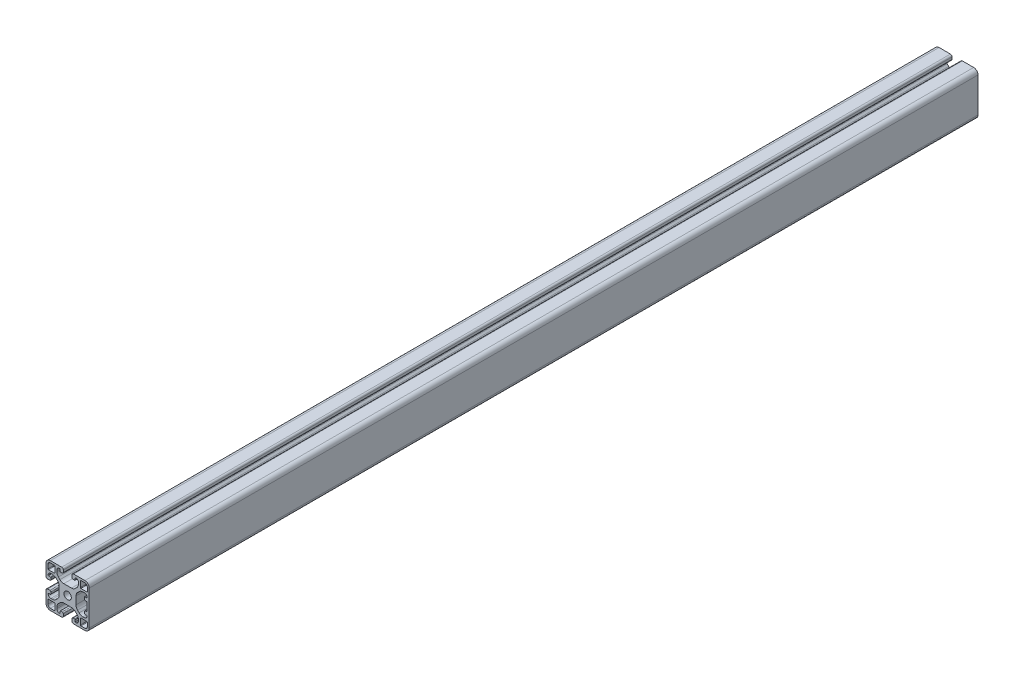
SolidWorks part; units mm, degrees
ref_plane "Piano frontale" through (0, 0, 0) normal (0, 0, 1) x (1, 0, 0)
ref_plane "Piano superiore" through (0, 0, 0) normal (0, 1, 0) x (1, 0, 0)
ref_plane "Piano destro" through (0, 0, 0) normal (1, 0, 0) x (0, 0, -1)
ref_plane "Piano1" through (0, 0, -340) normal (0, 0, -1) x (-1, 0, 0)
sketch "Schizzo1" plane through (0, 0, -340) normal (0, 0, -1) x (-1, 0, 0)
  line L0 (-12.3, -18.2) -> (-16, -18.2)
  line L1 (-18.2, -16) -> (-18.2, -12.3)
  line L2 (-17.7, -11.8) -> (-12.3, -11.8)
  line L3 (-11.8, -12.3) -> (-11.8, -17.7)
  line L4 (-11.8, 17.7) -> (-11.8, 12.3)
  line L5 (-12.3, 11.8) -> (-17.7, 11.8)
  line L6 (-18.2, 12.3) -> (-18.2, 16)
  line L7 (-16, 18.2) -> (-12.3, 18.2)
  line L8 (18.2, 16) -> (18.2, 12.3)
  line L9 (17.7, 11.8) -> (12.3, 11.8)
  line L10 (11.8, 12.3) -> (11.8, 17.7)
  line L11 (12.3, 18.2) -> (16, 18.2)
  line L12 (6.5, -15.5) -> (5, -15.5)
  line L13 (4, -16.5) -> (4, -18.5)
  line L14 (5.5, -20) -> (16, -20)
  line L15 (20, -16) -> (20, -5.5)
  line L16 (18.5, -4) -> (16.5, -4)
  line L17 (15.5, -5) -> (15.5, -6.5)
  line L18 (16, -7) -> (17.55, -7)
  line L19 (18, -7.45) -> (18, -7.5)
  line L20 (15.5, -10) -> (14.1924, -10)
  line L21 (10.6569, -8.5355) -> (9.2145, -7.0931)
  line L22 (7.75, -3.5576) -> (7.75, 3.5576)
  line L23 (9.2145, 7.0931) -> (10.6569, 8.5355)
  line L24 (14.1924, 10) -> (15.5, 10)
  line L25 (18, 7.5) -> (18, 7.45)
  line L26 (17.55, 7) -> (16, 7)
  line L27 (15.5, 6.5) -> (15.5, 5)
  line L28 (16.5, 4) -> (18.5, 4)
  line L29 (20, 5.5) -> (20, 16)
  line L30 (16, 20) -> (5.5, 20)
  line L31 (4, 18.5) -> (4, 16.5)
  line L32 (5, 15.5) -> (6.5, 15.5)
  line L33 (7, 16) -> (7, 17.55)
  line L34 (7.45, 18) -> (7.5, 18)
  line L35 (10, 15.5) -> (10, 14.1924)
  line L36 (8.5355, 10.6569) -> (7.0931, 9.2145)
  line L37 (3.5576, 7.75) -> (-3.5576, 7.75)
  line L38 (-7.0931, 9.2145) -> (-8.5355, 10.6569)
  line L39 (-10, 14.1924) -> (-10, 15.5)
  line L40 (-7.5, 18) -> (-7.45, 18)
  line L41 (-7, 17.55) -> (-7, 16)
  line L42 (-6.5, 15.5) -> (-5, 15.5)
  line L43 (-4, 16.5) -> (-4, 18.5)
  line L44 (-5.5, 20) -> (-16, 20)
  line L45 (-20, 16) -> (-20, -16)
  line L46 (-16, -20) -> (-5.5, -20)
  line L47 (-4, -18.5) -> (-4, -16.5)
  line L48 (-5, -15.5) -> (-6.5, -15.5)
  line L49 (-7, -16) -> (-7, -17.55)
  line L50 (-7.45, -18) -> (-7.5, -18)
  line L51 (-10, -15.5) -> (-10, -14.1924)
  line L52 (-8.5355, -10.6569) -> (-7.0931, -9.2145)
  line L53 (-3.5576, -7.75) -> (3.5576, -7.75)
  line L54 (7.0931, -9.2145) -> (8.5355, -10.6569)
  line L55 (10, -14.1924) -> (10, -15.5)
  line L56 (7.5, -18) -> (7.45, -18)
  line L57 (7, -17.55) -> (7, -16)
  line L58 (18.2, -12.3) -> (18.2, -16)
  line L59 (16, -18.2) -> (12.3, -18.2)
  line L60 (11.8, -17.7) -> (11.8, -12.3)
  line L61 (12.3, -11.8) -> (17.7, -11.8)
  line L62 (-16, 7) -> (-17.5, 7)
  line L63 (-15.5, 10) -> (-14.1924, 10)
  line L64 (-10.6569, 8.5355) -> (-9.2145, 7.0931)
  line L65 (-7.75, 3.5576) -> (-7.75, -3.5576)
  line L66 (-9.2145, -7.0931) -> (-10.6569, -8.5355)
  line L67 (-14.1924, -10) -> (-15.5, -10)
  line L68 (-17.5, -7) -> (-16, -7)
  line L69 (-15.5, -6.5) -> (-15.5, -5)
  line L70 (-16.5, -4) -> (-17.5, -4)
  line L71 (-18, -3.5) -> (-18, 3.5)
  line L72 (-17.5, 4) -> (-16.5, 4)
  line L73 (-15.5, 5) -> (-15.5, 6.5)
  arc A0 (-16, -18.2) -> (-18.2, -16) centre (-16, -16) cw
  arc A1 (-18.2, -12.3) -> (-17.7, -11.8) centre (-17.7, -12.3) cw
  arc A2 (-12.3, -11.8) -> (-11.8, -12.3) centre (-12.3, -12.3) cw
  arc A3 (-11.8, -17.7) -> (-12.3, -18.2) centre (-12.3, -17.7) cw
  arc A4 (-12.3, 18.2) -> (-11.8, 17.7) centre (-12.3, 17.7) cw
  arc A5 (-11.8, 12.3) -> (-12.3, 11.8) centre (-12.3, 12.3) cw
  arc A6 (-17.7, 11.8) -> (-18.2, 12.3) centre (-17.7, 12.3) cw
  arc A7 (-18.2, 16) -> (-16, 18.2) centre (-16, 16) cw
  arc A8 (16, 18.2) -> (18.2, 16) centre (16, 16) cw
  arc A9 (18.2, 12.3) -> (17.7, 11.8) centre (17.7, 12.3) cw
  arc A10 (12.3, 11.8) -> (11.8, 12.3) centre (12.3, 12.3) cw
  arc A11 (11.8, 17.7) -> (12.3, 18.2) centre (12.3, 17.7) cw
  arc A12 (5, -15.5) -> (4, -16.5) centre (5, -16.5) ccw
  arc A13 (4, -18.5) -> (5.5, -20) centre (5.5, -18.5) ccw
  arc A14 (16, -20) -> (20, -16) centre (16, -16) ccw
  arc A15 (20, -5.5) -> (18.5, -4) centre (18.5, -5.5) ccw
  arc A16 (16.5, -4) -> (15.5, -5) centre (16.5, -5) ccw
  arc A17 (15.5, -6.5) -> (16, -7) centre (16, -6.5) ccw
  arc A18 (17.55, -7) -> (18, -7.45) centre (17.55, -7.45) cw
  arc A19 (18, -7.5) -> (15.5, -10) centre (15.5, -7.5) cw
  arc A20 (14.1924, -10) -> (10.6569, -8.5355) centre (14.1924, -5) cw
  arc A21 (9.2145, -7.0931) -> (7.75, -3.5576) centre (12.75, -3.5576) cw
  arc A22 (7.75, 3.5576) -> (9.2145, 7.0931) centre (12.75, 3.5576) cw
  arc A23 (10.6569, 8.5355) -> (14.1924, 10) centre (14.1924, 5) cw
  arc A24 (15.5, 10) -> (18, 7.5) centre (15.5, 7.5) cw
  arc A25 (18, 7.45) -> (17.55, 7) centre (17.55, 7.45) cw
  arc A26 (16, 7) -> (15.5, 6.5) centre (16, 6.5) ccw
  arc A27 (15.5, 5) -> (16.5, 4) centre (16.5, 5) ccw
  arc A28 (18.5, 4) -> (20, 5.5) centre (18.5, 5.5) ccw
  arc A29 (20, 16) -> (16, 20) centre (16, 16) ccw
  arc A30 (5.5, 20) -> (4, 18.5) centre (5.5, 18.5) ccw
  arc A31 (4, 16.5) -> (5, 15.5) centre (5, 16.5) ccw
  arc A32 (6.5, 15.5) -> (7, 16) centre (6.5, 16) ccw
  arc A33 (7, 17.55) -> (7.45, 18) centre (7.45, 17.55) cw
  arc A34 (7.5, 18) -> (10, 15.5) centre (7.5, 15.5) cw
  arc A35 (10, 14.1924) -> (8.5355, 10.6569) centre (5, 14.1924) cw
  arc A36 (7.0931, 9.2145) -> (3.5576, 7.75) centre (3.5576, 12.75) cw
  arc A37 (-3.5576, 7.75) -> (-7.0931, 9.2145) centre (-3.5576, 12.75) cw
  arc A38 (-8.5355, 10.6569) -> (-10, 14.1924) centre (-5, 14.1924) cw
  arc A39 (-10, 15.5) -> (-7.5, 18) centre (-7.5, 15.5) cw
  arc A40 (-7.45, 18) -> (-7, 17.55) centre (-7.45, 17.55) cw
  arc A41 (-7, 16) -> (-6.5, 15.5) centre (-6.5, 16) ccw
  arc A42 (-5, 15.5) -> (-4, 16.5) centre (-5, 16.5) ccw
  arc A43 (-4, 18.5) -> (-5.5, 20) centre (-5.5, 18.5) ccw
  arc A44 (-16, 20) -> (-20, 16) centre (-16, 16) ccw
  arc A45 (-20, -16) -> (-16, -20) centre (-16, -16) ccw
  arc A46 (-5.5, -20) -> (-4, -18.5) centre (-5.5, -18.5) ccw
  arc A47 (-4, -16.5) -> (-5, -15.5) centre (-5, -16.5) ccw
  arc A48 (-6.5, -15.5) -> (-7, -16) centre (-6.5, -16) ccw
  arc A49 (-7, -17.55) -> (-7.45, -18) centre (-7.45, -17.55) cw
  arc A50 (-7.5, -18) -> (-10, -15.5) centre (-7.5, -15.5) cw
  arc A51 (-10, -14.1924) -> (-8.5355, -10.6569) centre (-5, -14.1924) cw
  arc A52 (-7.0931, -9.2145) -> (-3.5576, -7.75) centre (-3.5576, -12.75) cw
  arc A53 (3.5576, -7.75) -> (7.0931, -9.2145) centre (3.5576, -12.75) cw
  arc A54 (8.5355, -10.6569) -> (10, -14.1924) centre (5, -14.1924) cw
  arc A55 (10, -15.5) -> (7.5, -18) centre (7.5, -15.5) cw
  arc A56 (7.45, -18) -> (7, -17.55) centre (7.45, -17.55) cw
  arc A57 (7, -16) -> (6.5, -15.5) centre (6.5, -16) ccw
  arc A58 (17.7, -11.8) -> (18.2, -12.3) centre (17.7, -12.3) cw
  arc A59 (18.2, -16) -> (16, -18.2) centre (16, -16) cw
  arc A60 (12.3, -18.2) -> (11.8, -17.7) centre (12.3, -17.7) cw
  arc A61 (11.8, -12.3) -> (12.3, -11.8) centre (12.3, -12.3) cw
  circle A62 centre (0, 0) radius 3.4
  arc A63 (-15.5, 6.5) -> (-16, 7) centre (-16, 6.5) ccw
  arc A64 (-17.5, 7) -> (-18, 7.5) centre (-17.5, 7.5) cw
  arc A65 (-18, 7.5) -> (-15.5, 10) centre (-15.5, 7.5) cw
  arc A66 (-14.1924, 10) -> (-10.6569, 8.5355) centre (-14.1924, 5) cw
  arc A67 (-9.2145, 7.0931) -> (-7.75, 3.5576) centre (-12.75, 3.5576) cw
  arc A68 (-7.75, -3.5576) -> (-9.2145, -7.0931) centre (-12.75, -3.5576) cw
  arc A69 (-10.6569, -8.5355) -> (-14.1924, -10) centre (-14.1924, -5) cw
  arc A70 (-15.5, -10) -> (-18, -7.5) centre (-15.5, -7.5) cw
  arc A71 (-18, -7.5) -> (-17.5, -7) centre (-17.5, -7.5) cw
  arc A72 (-16, -7) -> (-15.5, -6.5) centre (-16, -6.5) ccw
  arc A73 (-15.5, -5) -> (-16.5, -4) centre (-16.5, -5) ccw
  arc A74 (-17.5, -4) -> (-18, -3.5) centre (-17.5, -3.5) cw
  arc A75 (-18, 3.5) -> (-17.5, 4) centre (-17.5, 3.5) cw
  arc A76 (-16.5, 4) -> (-15.5, 5) centre (-16.5, 5) ccw
extrude "Estrusione-Estrusione1" add sketch "Schizzo1" against normal blind 822
